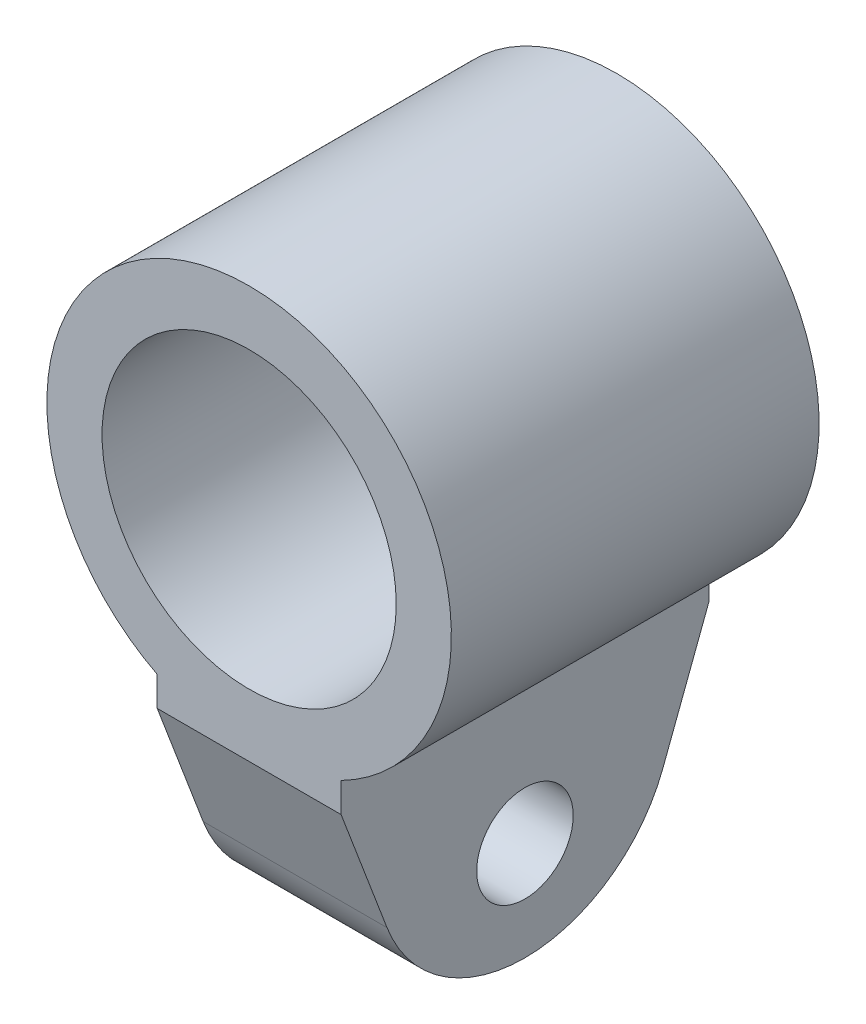
SolidWorks part; units mm, degrees
ref_plane "Front Plane" through (0, 0, 0) normal (0, 0, 1) x (1, 0, 0)
ref_plane "Top Plane" through (0, 0, 0) normal (0, 1, 0) x (1, 0, 0)
ref_plane "Right Plane" through (0, 0, 0) normal (1, 0, 0) x (0, 0, -1)
sketch "Sketch1" plane through (0, 0, 0) normal (0, 0, 1) x (1, 0, 0)
  circle A1 centre (0, 41.8069) radius 16
  circle A2 centre (0, 41.8069) radius 22
  point P0 (0, 41.8069)
  dimension "D3" = 32
  dimension "D1" = 44
  dimension "D2" = 41.8069
extrude "Boss-Extrude1" add sketch "Sketch1" along normal mid plane 40
ref_plane "Plane1" through (0, 19, 0) normal (0, 1, 0) x (1, 0, 0)
sketch "Sketch5" plane through (0, 19, 0) normal (0, 1, 0) x (1, 0, 0)
  line L0 (16, 20) -> (-16, 20) construction
  line L1 (-10, 20) -> (10, 20)
  line L2 (-10, 20) -> (-10, -20)
  line L3 (-10, -20) -> (10, -20)
  line L4 (10, 20) -> (10, -20)
  line L5 (-10, 20) -> (10, -20) construction
  line L6 (-10, -20) -> (10, 20) construction
  point P0 (0, 0)
  dimension "D1" = 20
extrude "Boss-Extrude2" add sketch "Sketch5" along normal up to next
sketch "Sketch6" plane through (0, 0, 0) normal (1, 0, 0) x (0, 0, -1)
  line L0 (-20, 19) -> (-15, 5.8427)
  line L1 (22, 19) -> (-22, 19) construction
  line L2 (15, 5.8427) -> (20, 19)
  line L3 (20, 22.2109) -> (20, 19) construction
  line L4 (-20, 22.2109) -> (-20, 19) construction
  line L5 (-20, 19) -> (20, 19)
  circle A0 centre (0, 6.293) radius 5.25
  arc A1 (-15, 5.8427) -> (15, 5.8427) centre (0, 11.543) ccw
  dimension "D1" = 10.5
  dimension "D2" = 6.293
  dimension "D3" = 15
extrude "Boss-Extrude3" add sketch "Sketch6" along normal mid plane 20
equation "\"column angle\" = 45deg "
equation "\"short_bearing_outer_width\" = 10mm "
equation "\"wheel base\" = 1561mm "
equation "\"track\" = 1354mm "
equation "\"turning radius\" = 2000mm "
equation "\"turn to lock\" = 0.75mm "
equation "\"steering arm length\" = 100mm "
equation "\"primary shaft small diameter\" = 16mm "
equation "\"primary shaft large diameter\" = 24mm "
equation "\"secondary shaft small diameter\" = 16mm "
equation "\"secondary shaft large diameter\" = 25mm "
equation "\"steering column length\" = 555mm "
equation "\"keyway_height\" = 1.39mm "
equation "\"keyway_width\" = 2.78mm "
equation "\"keyway_length\" = 30mm "
equation "\"steering wheel bolt width\" = 6mm "
equation "\"steering wheel bolt length\" = 40mm "
equation "\"bushing length\" = 40mm "
equation "\"bushing thickness\" = 3mm "
equation "\"u_joint clearance\" = 30mm "
equation "\"u_joint thickness\" = 7.5mm "
equation "\"horizontal shaft length\" = 90mm "
equation "\"column bushing diameter\" = \"primary shaft small diameter\" + 4 "
equation "\"column bushing distance\" = \"steering column length\"/4 "
equation "\"pinion width\" = 26.5mm "
equation "\"pin hole diameter\" = 10mm "
equation "\"rack hole to hole\" = 500mm "
equation "\"rack length\" = \"rack hole to hole\" + \"pin hole diameter\"*2 "
equation "\"max turning angle\" = atn(\"wheel base\" / (\"turning radius\" - 0.5 * \"track\")) "
equation "\"max travel\" = 2 * \"steering arm length\" * sin(0.5 * \"max turning angle\") "
equation "\"pitch diameter\" = \"max travel\"/(pi * \"turn to lock\") "
equation "\"number of teeth\" = 18mm "
equation "\"pressure angle\" = 20deg "
equation "\"module\" = \"pitch diameter\" / \"number of teeth\" "
equation "\"tie rod length\" = 305mm "
equation "\"tie rod inner diameter\" = 6.6mm "
equation "\"tie rod outer diameter\" = 8.1mm "
equation "\"D3@Sketch1\"=\"primary shaft large diameter\"+8"
equation "\"D1@Sketch1\"=\"primary shaft large diameter\"+20"
